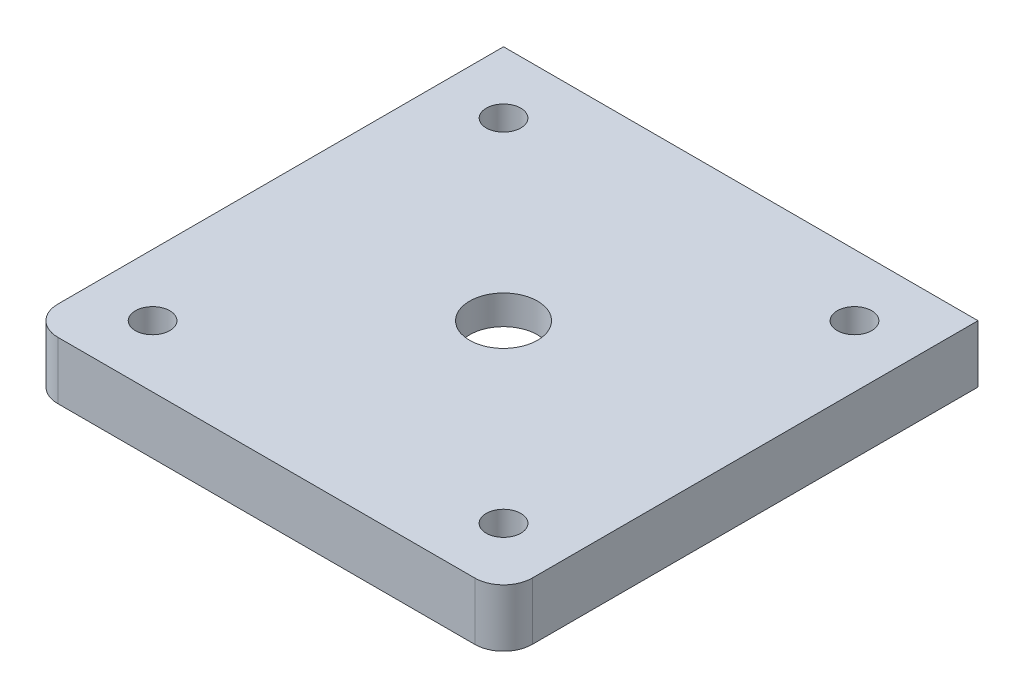
SolidWorks part; units mm, degrees
ref_plane "Front Plane" through (0, 0, 0) normal (0, 0, 1) x (1, 0, 0)
ref_plane "Top Plane" through (0, 0, 0) normal (0, 1, 0) x (1, 0, 0)
ref_plane "Right Plane" through (0, 0, 0) normal (1, 0, 0) x (0, 0, -1)
sketch "Sketch1" plane through (0, 0, 0) normal (0, 1, 0) x (1, 0, 0)
  line L0 (0, 20.955) -> (0, -20.955) construction
  line L1 (-20.955, 20.955) -> (20.955, 20.955)
  line L2 (-20.955, 20.955) -> (-20.955, -20.955)
  line L3 (-20.955, -20.955) -> (20.955, -20.955)
  line L4 (20.955, 20.955) -> (20.955, -20.955)
  line L5 (-20.955, 20.955) -> (20.955, -20.955) construction
  line L6 (-20.955, -20.955) -> (20.955, 20.955) construction
  line L7 (-15.5, 15.5) -> (15.5, 15.5) construction
  line L8 (-15.5, 15.5) -> (-15.5, -15.5) construction
  line L9 (-15.5, -15.5) -> (15.5, -15.5) construction
  line L10 (15.5, 15.5) -> (15.5, -15.5) construction
  line L11 (-15.5, 15.5) -> (15.5, -15.5) construction
  line L12 (-15.5, -15.5) -> (15.5, 15.5) construction
  line L13 (-20.955, 0) -> (20.955, 0) construction
  circle A0 centre (-15.5, 15.5) radius 1.524
  circle A1 centre (15.5, 15.5) radius 1.524
  circle A2 centre (15.5, -15.5) radius 1.524
  circle A3 centre (-15.5, -15.5) radius 1.524
  point P0 (0, 0)
  point P6 (0, 0)
  dimension "D4" = 3.048
  dimension "D1" = 41.91
  dimension "D2" = 41.91
  dimension "D3" = 31
extrude "Boss-Extrude1" add sketch "Sketch1" along normal blind 5.08
sketch "Sketch2" plane through (0, 0, -20.955) normal (0, 0, -1) x (-1, 0, 0)
  line L0 (20.955, 5.08) -> (20.955, 0) construction
  line L1 (-20.955, 5.08) -> (20.955, 5.08)
  line L2 (-20.955, 5.08) -> (-20.955, -19.42)
  line L3 (-20.955, -19.42) -> (20.955, -19.42)
  line L4 (20.955, 5.08) -> (20.955, -19.42)
  dimension "D1" = 24.5
extrude "Boss-Extrude2" add sketch "Sketch2" along normal blind 5.08
sketch "Sketch4" plane through (0, 0, 0) normal (0, -1, 0) x (1, 0, 0)
  circle A0 centre (0, 0) radius 11.5
  dimension "D1" = 23
extrude "Cut-Extrude1" cut sketch "Sketch4" against normal blind 2.5
sketch "Sketch5" plane through (0, 2.5, 0) normal (0, -1, 0) x (1, 0, 0)
  circle A0 centre (0, 0) radius 3
  dimension "D1" = 6
extrude "Cut-Extrude2" cut sketch "Sketch5" against normal through all
sketch "Sketch6" plane through (0, -19.42, 0) normal (0, -1, 0) x (1, 0, 0)
  line L0 (0, -20.955) -> (0, -61.6204) construction
  line L1 (20.955, -20.955) -> (-20.955, -20.955) construction
  line L2 (16.8275, -41.2877) -> (16.8275, -24.4602)
  line L3 (16.8275, -24.4602) -> (-16.8275, -24.4602)
  line L4 (-16.8275, -24.4602) -> (-16.8275, -41.2877)
  arc A0 (-16.8275, -41.2877) -> (16.8275, -41.2877) centre (0, -41.2877) ccw
  point P5 (0, -41.2877)
  dimension "D2" = 33.655
  dimension "D1" = 40.6654
extrude "Boss-Extrude3" add sketch "Sketch6" against normal blind 6.35
sketch "Sketch7" plane through (0, 0, 0) normal (1, 0, 0) x (0, 0, -1)
  line L0 (26.035, -19.42) -> (26.035, 5.08) construction
  line L1 (58.1152, -13.07) -> (41.2877, -13.07) construction
  line L2 (26.035, -13.07) -> (41.2877, -13.07) construction
  line L3 (26.035, -13.07) -> (26.035, 5.08)
  line L4 (49.7015, -13.07) -> (41.2877, -13.07)
  line L5 (26.035, -13.07) -> (41.2877, -13.07)
  line L6 (49.7015, -13.07) -> (26.035, 5.08)
extrude "Boss-Extrude4" add sketch "Sketch7" along normal blind 3.175 and the other way blind 3.175
sketch "Sketch8" plane through (-3.175, 0, 0) normal (-1, 0, 0) x (0, 0, 1)
  line L6 (-27.94, 1.2183) -> (-44.0871, -11.165)
  line L7 (-44.0871, -11.165) -> (-27.94, -11.165)
  line L8 (-27.94, -11.165) -> (-27.94, 1.2183)
  line L9 (-27.94, 1.2183) -> (-44.0871, -11.165)
  line L10 (-44.0871, -11.165) -> (-27.94, -11.165)
  line L11 (-27.94, -11.165) -> (-27.94, 1.2183)
  dimension "D1" = 1.905
extrude "Cut-Extrude3" cut sketch "Sketch8" against normal blind 1.27
fillet "Fillet2" radius 0.635 3 edges at (-2.54, -11.165, -44.0871) (-2.54, 1.2183, -27.94) (-2.54, -11.165, -27.94)
fillet "Fillet6" radius 1.27 12 edges at (-10.0012, -13.07, -26.035) (-3.175, -13.07, -37.8682) (-3.175, -3.995, -26.035) (16.8275, -16.245, -26.035) (10.0013, -13.07, -26.035) (16.8275, -13.07, -33.6613) (0, -13.07, -58.1152) (-16.8275, -13.07, -33.6613) (-16.8275, -16.245, -26.035) (0, -13.07, -49.7015) (3.175, -3.995, -26.035) (3.175, -13.07, -37.8682)
fillet "Fillet7" radius 2.54 6 edges at (12.7, 5.08, -26.035) (-12.7, 5.08, -26.035) (20.955, 2.54, 20.955) (-20.955, 2.54, 20.955) (20.955, -7.17, -26.035) (-20.955, -7.17, -26.035)
mirror "Mirror2" about plane through (0, 0, 0) normal (1, 0, 0) of "Fillet2", "Cut-Extrude3"
sketch "Sketch10" plane through (0, -19.42, 0) normal (0, -1, 0) x (1, 0, 0)
  circle A0 centre (0, -41.2877) radius 16.8275
  circle A1 centre (0, -41.2877) radius 10.795
  dimension "D1" = 21.59
extrude "Boss-Extrude5" add sketch "Sketch10" along normal blind 25.4
sketch "Sketch11" plane through (0, 0, -20.955) normal (0, 0, 1) x (1, 0, 0)
  line L1 (42.0465, -53.7198) -> (-42.0465, -53.7198)
  line L2 (42.0465, -53.7198) -> (42.0465, 21.6885)
  line L3 (42.0465, 21.6885) -> (-42.0465, 21.6885)
  line L4 (-42.0465, -53.7198) -> (-42.0465, 21.6885)
  line L5 (42.0465, -53.7198) -> (-42.0465, 21.6885) construction
  line L6 (42.0465, 21.6885) -> (-42.0465, -53.7198) construction
  point P0 (0, -16.0156)
extrude "Cut-Extrude4" cut sketch "Sketch11" against normal through all
